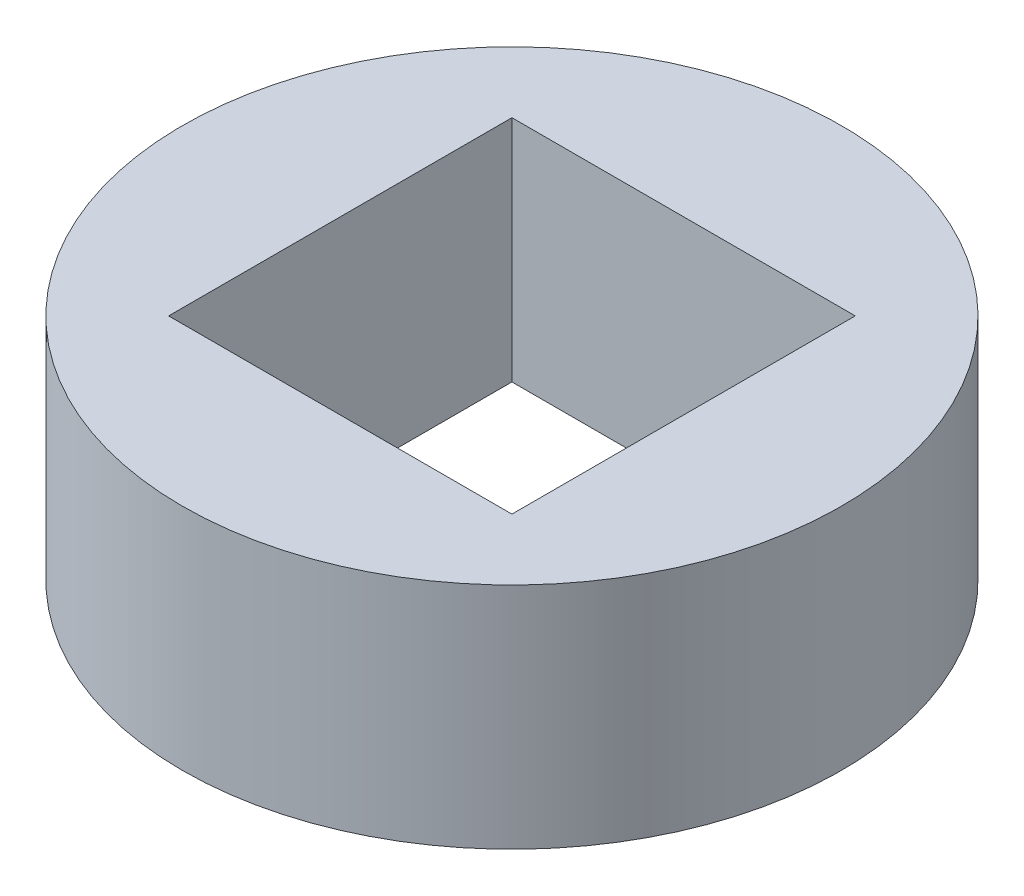
SolidWorks part; units mm, degrees
ref_plane "Front Plane" through (0, 0, 0) normal (0, 0, 1) x (1, 0, 0)
ref_plane "Top Plane" through (0, 0, 0) normal (0, 1, 0) x (1, 0, 0)
ref_plane "Right Plane" through (0, 0, 0) normal (1, 0, 0) x (0, 0, -1)
sketch "Sketch1" plane through (0, 0, 0) normal (0, 1, 0) x (1, 0, 0)
  line L1 (-4.7625, -4.7625) -> (4.7625, -4.7625)
  line L2 (-4.7625, -4.7625) -> (-4.7625, 4.7625)
  line L3 (-4.7625, 4.7625) -> (4.7625, 4.7625)
  line L4 (4.7625, -4.7625) -> (4.7625, 4.7625)
  line L5 (-4.7625, -4.7625) -> (4.7625, 4.7625) construction
  line L6 (-4.7625, 4.7625) -> (4.7625, -4.7625) construction
  circle A0 centre (0, 0) radius 9.144
  dimension "D1" = 18.288
  dimension "D2" = 9.525
  dimension "D3" = 9.525
extrude "Boss-Extrude1" add sketch "Sketch1" along normal blind 6.35
